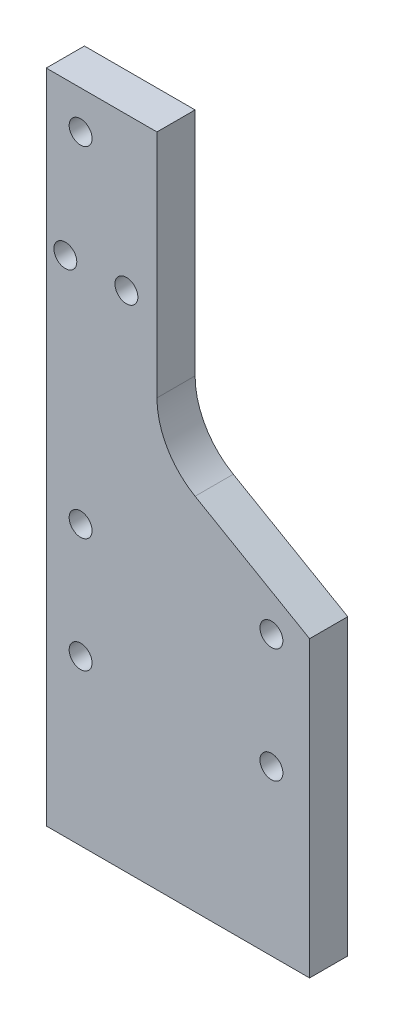
SolidWorks part; units mm, degrees
material "AISI 321 Отожженная нержавеющая сталь (SS)"
ref_plane "Спереди" through (0, 0, 0) normal (0, 0, 1) x (1, 0, 0)
ref_plane "Сверху" through (0, 0, 0) normal (0, 1, 0) x (1, 0, 0)
ref_plane "Справа" through (0, 0, 0) normal (1, 0, 0) x (0, 0, -1)
sketch "Эскиз1" plane through (0, 0, 0) normal (0, 0, 1) x (1, 0, 0)
  line L0 (0, 0) -> (-69, 0)
  line L1 (-69, 0) -> (-69, 189)
  line L2 (-69, 189) -> (-40, 189)
  line L3 (-40, 189) -> (-40, 128.641)
  line L4 (-30, 111.3205) -> (0, 94)
  line L5 (0, 94) -> (0, 0)
  line L6 (-60, 60) -> (-60, 90) construction
  line L7 (-60, 60) -> (-10, 60) construction
  line L8 (-60, 60) -> (-60, 10) construction
  line L9 (-60, 10) -> (-10, 10) construction
  line L10 (-10, 60) -> (-10, 10) construction
  line L11 (-60, 90) -> (-10, 90) construction
  line L12 (-10, 90) -> (-10, 60) construction
  line L13 (-64, 149) -> (-48, 149) construction
  line L14 (-69, 179) -> (-60, 179) construction
  line L15 (-60, 179) -> (-60, 189) construction
  arc A0 (-40, 128.641) -> (-30, 111.3205) centre (-20, 128.641) ccw
  circle A1 centre (-10, 10) radius 3
  circle A2 centre (-60, 10) radius 3
  circle A3 centre (-60, 60) radius 3
  circle A4 centre (-10, 60) radius 3
  circle A5 centre (-60, 90) radius 3
  circle A6 centre (-10, 90) radius 3
  circle A7 centre (-64, 149) radius 3
  circle A8 centre (-48, 149) radius 3
  circle A9 centre (-60, 179) radius 3
  dimension "D6" = 20
  dimension "D11" = 6
  dimension "D13" = 5
  dimension "D1" = 69
  dimension "D2" = 189
  dimension "D3" = 29
  dimension "D4" = 94
  dimension "D5" = 60
  dimension "D7" = 10
  dimension "D8" = 9
  dimension "D9" = 50
  dimension "D10" = 50
  dimension "D12" = 30
  dimension "D14" = 16
  dimension "D15" = 40
  dimension "D16" = 9
  dimension "D17" = 10
extrude "Бобышка-Вытянуть1" add sketch "Эскиз1" along normal blind 10
sketch "Эскиз2" plane through (0, 0, 0) normal (0, -1, 0) x (1, 0, 0)
  line L1 (-69, 10) -> (0, 10)
  line L2 (-69, 10) -> (-69, 0)
  line L3 (-69, 0) -> (0, 0)
  line L4 (0, 10) -> (0, 0)
extrude "Бобышка-Вытянуть2" [suppressed] add sketch "Эскиз2" along normal blind 60 separate body
sketch "Эскиз3" [suppressed] plane through (0, 0, 10) normal (0, 0, 1) x (1, 0, 0)
  line L0 (0, -60) -> (-69, -60) construction
  line L1 (-9.5, -10) -> (-59.5, -10) construction
  line L2 (-9.5, -10) -> (-9.5, -45) construction
  line L3 (-9.5, -45) -> (-59.5, -45) construction
  line L4 (-59.5, -10) -> (-59.5, -45) construction
  line L5 (-34.5, -60) -> (-34.5, -45) construction
  circle A0 centre (-9.5, -45) radius 3
  circle A1 centre (-59.5, -45) radius 3
  circle A2 centre (-59.5, -10) radius 3
  circle A3 centre (-9.5, -10) radius 3
  circle A4 centre (-10, 10) radius 3 construction
  dimension "D1" = 15
  dimension "D2" = 35
  dimension "D3" = 50
extrude "Вырез-Вытянуть1" [suppressed] cut sketch "Эскиз3" against normal through all
sketch "Эскиз4" plane through (0, 0, 10) normal (0, 0, 1) x (1, 0, 0)
  line L0 (0, 0) -> (0, 94) construction
  line L1 (-69, 0) -> (0, 0)
  line L2 (-69, 0) -> (-69, 17)
  line L3 (-69, 17) -> (0, 17)
  line L4 (0, 0) -> (0, 17)
  dimension "D1" = 17
extrude "Вырез-Вытянуть2" cut sketch "Эскиз4" against normal through all
